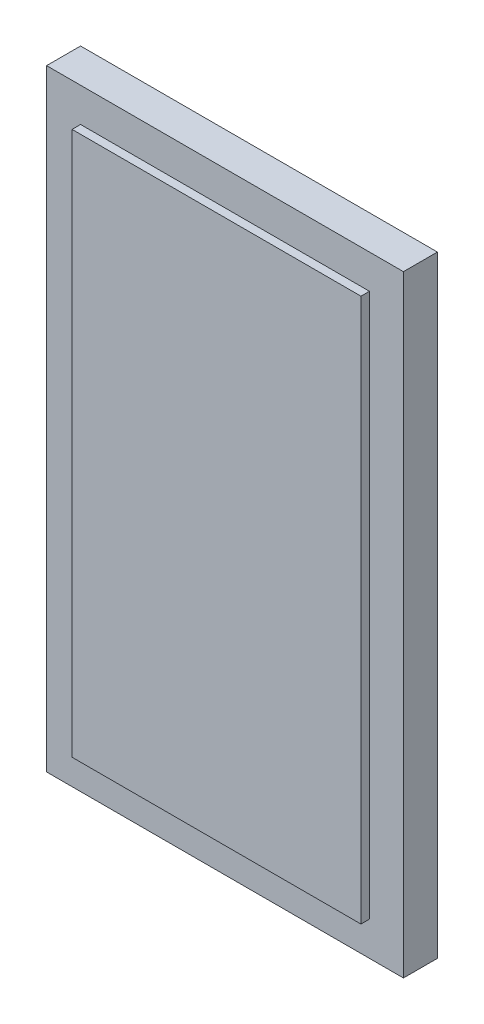
SolidWorks part; units mm, degrees
ref_plane "Front Plane" through (0, 0, 0) normal (0, 0, 1) x (1, 0, 0)
ref_plane "Top Plane" through (0, 0, 0) normal (0, 1, 0) x (1, 0, 0)
ref_plane "Right Plane" through (0, 0, 0) normal (1, 0, 0) x (0, 0, -1)
sketch "Sketch1" plane through (0, 0, 0) normal (0, 0, 1) x (1, 0, 0)
  line L1 (0, 0) -> (105, 0)
  line L2 (0, 0) -> (0, 180)
  line L3 (0, 180) -> (105, 180)
  line L4 (105, 0) -> (105, 180)
  dimension "D1" = 105
  dimension "D2" = 180
extrude "Boss-Extrude1" add sketch "Sketch1" along normal blind 10
sketch "Sketch2" plane through (0, 0, 10) normal (0, 0, 1) x (1, 0, 0)
  line L8 (10, 170) -> (10, 10)
  line L9 (10, 10) -> (95, 10)
  line L10 (95, 10) -> (95, 170)
  line L11 (95, 170) -> (10, 170)
  line L12 (10, 170) -> (10, 10)
  line L13 (10, 10) -> (95, 10)
  line L14 (95, 10) -> (95, 170)
  line L15 (95, 170) -> (10, 170)
  dimension "D1" = 10
extrude "Boss-Extrude2" add sketch "Sketch2" along normal blind 2.5
